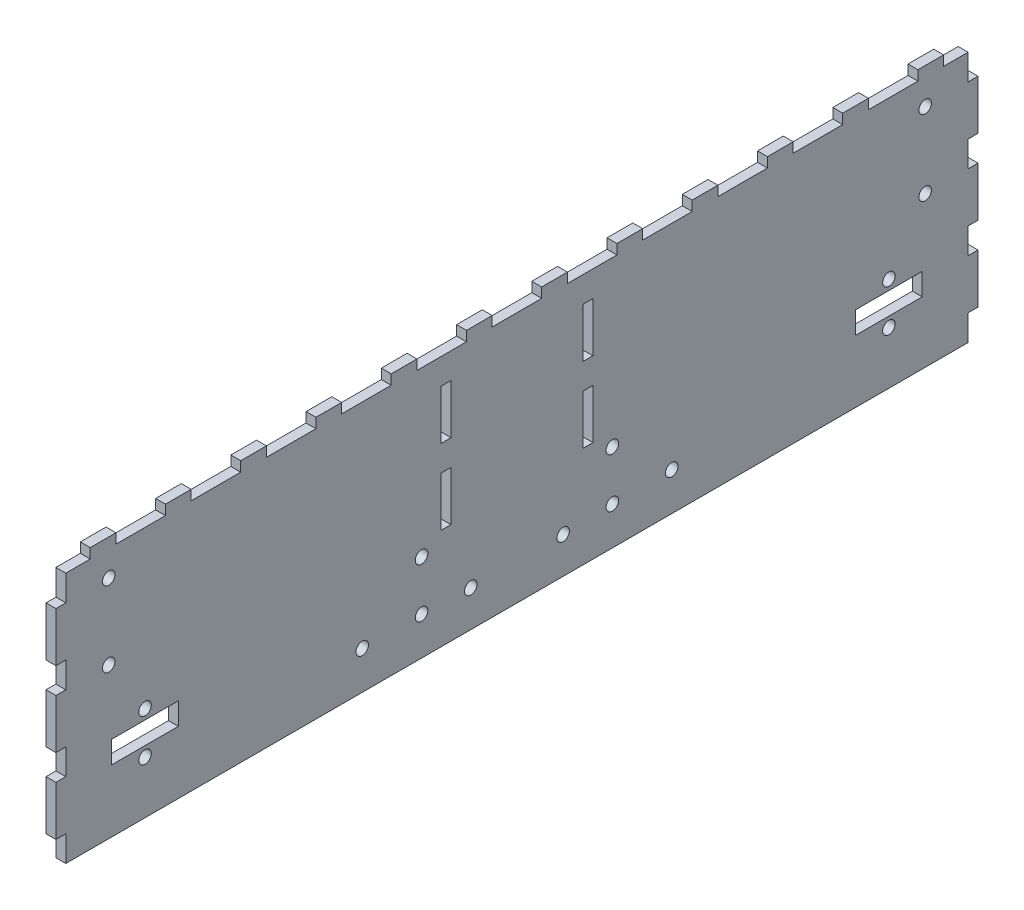
SolidWorks part; units mm, degrees
material "ENPH 253 Hardboard"
ref_plane "Front Plane" through (0, 0, 0) normal (0, 0, 1) x (1, 0, 0)
ref_plane "Top Plane" through (0, 0, 0) normal (0, 1, 0) x (1, 0, 0)
ref_plane "Right Plane" through (0, 0, 0) normal (1, 0, 0) x (0, 0, -1)
sketch "Sketch1" plane through (0, 0, 0) normal (1, 0, 0) x (0, 0, -1)
  line L1 (-139.7, 38.1) -> (139.7, 38.1)
  line L2 (-139.7, 38.1) -> (-139.7, -38.1)
  line L3 (-139.7, -38.1) -> (139.7, -38.1)
  line L4 (139.7, 38.1) -> (139.7, -38.1)
  line L5 (-139.7, 38.1) -> (139.7, -38.1) construction
  line L6 (-139.7, -38.1) -> (139.7, 38.1) construction
  point P0 (0, 0)
  dimension "D1" = 279.4
  dimension "D2" = 76.2
extrude "Boss-Extrude1" add sketch "Sketch1" against normal blind 3 contours L2 L3 L4 L1
sketch "Sketch3" plane through (-3, 0, 0) normal (-1, 0, 0) x (0, 0, 1)
  line L9 (-139.7, 38.1) -> (-136.7, 38.1)
  line L10 (-139.7, 38.1) -> (-139.7, 30.3)
  line L11 (-139.7, 30.3) -> (-136.7, 30.3)
  line L12 (-136.7, 38.1) -> (-136.7, 30.3)
  dimension "D9" = 7.8
  dimension "D10" = 3
extrude "Cut-Extrude1" cut sketch "Sketch3" against normal through all
pattern_linear "LPattern1" count 4 spacing 22.8 along (0, -1, 0) of "Cut-Extrude1"
mirror "Mirror1" about plane through (0, 0, 0) normal (0, 0, 1) of "LPattern1", "Cut-Extrude1"
sketch "Sketch5" plane through (-3, 0, 0) normal (-1, 0, 0) x (0, 0, 1)
  line L1 (-23, 30.3) -> (-20, 30.3)
  line L2 (-23, 30.3) -> (-23, 15.3)
  line L3 (-23, 15.3) -> (-20, 15.3)
  line L4 (-20, 30.3) -> (-20, 15.3)
  line L5 (136.7, 38.1) -> (-136.7, 38.1) construction
  line L6 (0, -1.65) -> (0, 1.65) construction
  dimension "D1" = 20
  dimension "D2" = 3
  dimension "D3" = 7.8
  dimension "D4" = 15
extrude "Cut-Extrude3" cut sketch "Sketch5" against normal blind 10
sketch "Sketch9" plane through (0, 38.1, 0) normal (0, 1, 0) x (1, 0, 0)
  line L0 (0, -136.7) -> (0, 136.7) construction
  line L1 (0, 129.3) -> (-3, 129.3)
  line L2 (0, 129.3) -> (0, 121.5)
  line L3 (0, 121.5) -> (-3, 121.5)
  line L4 (-3, 129.3) -> (-3, 121.5)
  line L5 (-3, -136.7) -> (-3, 136.7) construction
  line L6 (0, 136.7) -> (-3, 136.7) construction
  point P10 (-1.5, 129.3)
  dimension "D1" = 7.4
  dimension "D2" = 7.8
extrude "Boss-Extrude2" add sketch "Sketch9" along normal blind 3
pattern_linear "LPattern4" count 12 spacing 22.8 along (0, 0, 1) of "Boss-Extrude2"
pattern_linear "LPattern5" count 2 spacing 22.8 along (0, -1, 0) of "Cut-Extrude3"
mirror "Mirror2" about plane through (0, 0, 0) normal (0, 0, 1) of "LPattern5", "Cut-Extrude3"
hole_wizard "#6 Clearance Hole1" positions "Sketch10" profile "Sketch11" hole size "#6" standard "ANSI Inch" end condition up to next
sketch "Sketch10" plane through (0, 0, 0) normal (1, 0, 0) x (0, 0, -1)
  point P0 (-28.9, -11.55)
  point P3 (-28.9, -26.55)
  point P6 (28.9, -26.55)
  point P9 (28.9, -11.55)
  point P13 (-46.9, -26.55)
  point P16 (46.9, -26.55)
sketch "Sketch11" plane through (0, -11.55, 28.9) normal (0, 1, 0) x (0, 0, -1)
  line L0 (0, 0) -> (0, 3)
  line L1 (0, 3) -> (1.8986, 3)
  line L2 (1.8986, 3) -> (1.8986, 0)
  line L5 (1.8986, 0) -> (0, 0)
  line L11 (0, -6.35) -> (0, 107.95) construction
  dimension "Thru Hole Dia." = 3.7973
  dimension "Thru Hole Depth" = 3
sketch "Sketch12" plane through (0, 0, 0) normal (1, 0, 0) x (0, 0, -1)
  line L0 (0, 38.1) -> (0, -38.1) construction
  line L1 (-122.7, -12.55) -> (-102.7, -12.55) construction
  line L2 (-122.7, -12.55) -> (-122.7, -19.05) construction
  line L3 (-122.7, -19.05) -> (-102.7, -19.05) construction
  line L4 (-102.7, -12.55) -> (-102.7, -19.05) construction
  line L5 (-7.5, 38.1) -> (7.5, 38.1) construction
  line L6 (-136.7, -38.1) -> (136.7, -38.1) construction
  line L8 (-139.7, -15.3) -> (-139.7, -30.3) construction
  line L9 (-122.8, -12.45) -> (-122.8, -19.15)
  line L10 (-122.8, -19.15) -> (-102.6, -19.15)
  line L11 (-102.6, -12.45) -> (-102.6, -19.15)
  line L12 (-122.8, -12.45) -> (-102.6, -12.45)
  line L13 (102.7, -12.55) -> (102.7, -19.05) construction
  line L14 (122.7, -19.05) -> (102.7, -19.05) construction
  line L15 (122.7, -12.55) -> (102.7, -12.55) construction
  line L16 (122.8, -12.45) -> (102.6, -12.45)
  line L17 (102.6, -12.45) -> (102.6, -19.15)
  line L18 (122.8, -19.15) -> (102.6, -19.15)
  line L19 (122.8, -12.45) -> (122.8, -19.15)
  line L20 (122.7, -12.55) -> (122.7, -19.05) construction
  dimension "D1" = 20
  dimension "D2" = 17
  dimension "D3" = 19.05
  dimension "D4" = 6.5
  dimension "D5" = 0.1
extrude "Cut-Extrude4" cut sketch "Sketch12" against normal up to next
hole_wizard "#6 Clearance Hole2" positions "Sketch13" profile "Sketch14" hole size "#6" standard "ANSI Inch" end condition up to next
sketch "Sketch13" plane through (-3, 0, 0) normal (-1, 0, 0) x (0, 0, 1)
  line L0 (-122.8, -12.45) -> (-102.6, -12.45) construction
  line L1 (-102.6, -19.15) -> (-122.8, -19.15) construction
  line L2 (102.6, -12.45) -> (122.8, -12.45) construction
  line L3 (122.8, -19.15) -> (102.6, -19.15) construction
  point P0 (-112.7, -9.45)
  point P2 (-112.7, -22.15)
  point P4 (112.7, -22.15)
  point P6 (112.7, -9.45)
  point P14 (-112.7, -12.45)
  point P17 (112.7, -12.45)
  dimension "D1" = 3
  dimension "D2" = 3
  dimension "D3" = 3
  dimension "D4" = 3
sketch "Sketch14" plane through (-3, -9.45, -112.7) normal (0, 1, 0) x (0, 0, 1)
  line L0 (0, 0) -> (0, 3)
  line L1 (0, 3) -> (1.8986, 3)
  line L2 (1.8986, 3) -> (1.8986, 0)
  line L5 (1.8986, 0) -> (0, 0)
  line L11 (0, -6.35) -> (0, 107.95) construction
  dimension "Thru Hole Dia." = 3.7973
  dimension "Thru Hole Depth" = 3
hole_wizard "#6 Clearance Hole3" positions "Sketch18" profile "Sketch19" hole size "#6" standard "ANSI Inch" end condition through all
sketch "Sketch18" plane through (-3, 0, 0) normal (-1, 0, 0) x (0, 0, 1)
  point P0 (14, -27.1)
  point P2 (-14, -27.1)
sketch "Sketch19" plane through (-3, -27.1, 14) normal (0, 1, 0) x (0, 0, 1)
  line L0 (0, 0) -> (0, 3)
  line L1 (0, 3) -> (1.8986, 3)
  line L2 (1.8986, 3) -> (1.8986, 0)
  line L5 (1.8986, 0) -> (0, 0)
  line L11 (0, -6.35) -> (0, 107.95) construction
  dimension "Thru Hole Dia." = 3.7973
  dimension "Thru Hole Depth" = 3
hole_wizard "#6 Clearance Hole4" positions "Sketch21" profile "Sketch22" hole size "#6" standard "ANSI Inch" end condition through all
sketch "Sketch21" plane through (-3, 0, 0) normal (-1, 0, 0) x (0, 0, 1)
  line L1 (-139.7, 30.3) -> (-136.7, 30.3) construction
  line L2 (-139.7, 7.5) -> (-136.7, 7.5) construction
  line L3 (0, -1.65) -> (0, 1.65) construction
  point P0 (-123.7, 30.3)
  point P2 (-123.7, 7.5)
  point P19 (123.7, 7.5)
  point P20 (123.7, 30.3)
  dimension "D1" = 13
  dimension "D2" = 13
sketch "Sketch22" plane through (-3, 30.3, -123.7) normal (0, 1, 0) x (0, 0, 1)
  line L0 (0, 0) -> (0, 3)
  line L1 (0, 3) -> (1.8986, 3)
  line L2 (1.8986, 3) -> (1.8986, 0)
  line L5 (1.8986, 0) -> (0, 0)
  line L11 (0, -6.35) -> (0, 107.95) construction
  dimension "Thru Hole Dia." = 3.7973
  dimension "Thru Hole Depth" = 3
